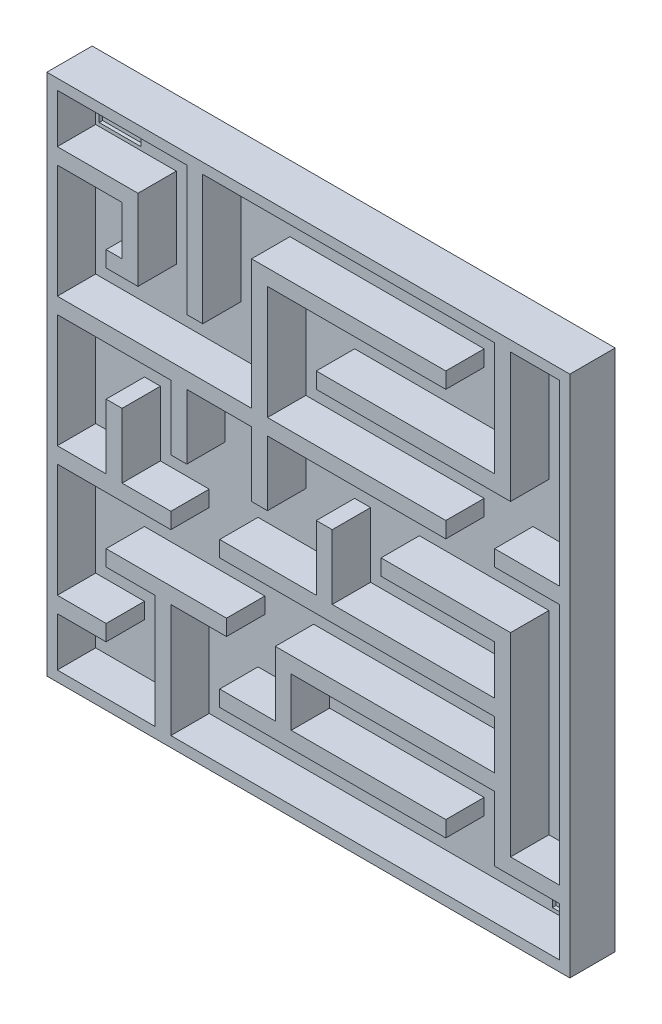
SolidWorks part; units mm, degrees
ref_plane "Front Plane" through (0, 0, 0) normal (0, 0, 1) x (1, 0, 0)
ref_plane "Top Plane" through (0, 0, 0) normal (0, 1, 0) x (1, 0, 0)
ref_plane "Right Plane" through (0, 0, 0) normal (1, 0, 0) x (0, 0, -1)
sketch "Sketch2" plane through (0, 0, 0) normal (0, 0, 1) x (1, 0, 0)
  line L1 (0, 0) -> (150, 0)
  line L2 (0, 0) -> (0, -150)
  line L3 (0, -150) -> (150, -150)
  line L4 (150, 0) -> (150, -150)
  dimension "D1" = 150
extrude "Boss-Extrude1" add sketch "Sketch2" along normal blind 2
sketch "Sketch3" plane through (0, 0, 2) normal (0, 0, 1) x (1, 0, 0)
  line L0 (140, -133) -> (140, -128.4286) construction
  line L1 (0, -3) -> (3, -3)
  line L2 (0, -3) -> (0, -150)
  line L3 (0, -150) -> (3, -150)
  line L4 (3, -3) -> (3, -150)
  line L5 (150, -150) -> (150, 0) construction
  line L10 (3, -147) -> (150, -147)
  line L15 (150, -147) -> (147, -147)
  line L16 (150, -147) -> (150, -3)
  line L17 (150, -3) -> (147, -3)
  line L18 (147, -147) -> (147, -3)
  line L19 (3, -147) -> (3, -150)
  line L20 (3, -150) -> (150, -150)
  line L21 (150, -147) -> (150, -150)
  line L22 (0, 0) -> (150, 0)
  line L23 (0, 0) -> (0, -3)
  line L24 (0, -3) -> (150, -3)
  line L25 (150, 0) -> (150, -3)
  line L26 (3, -17) -> (21.5714, -17)
  line L27 (3, -17) -> (3, -21.5714)
  line L28 (3, -21.5714) -> (21.5714, -21.5714)
  line L29 (21.5714, -17) -> (21.5714, -21.5714)
  line L30 (40.1429, -3) -> (44.7143, -3)
  line L31 (40.1429, -3) -> (40.1429, -40.1429)
  line L32 (40.1429, -40.1429) -> (44.7143, -40.1429)
  line L33 (44.7143, -3) -> (44.7143, -40.1429)
  line L34 (21.5714, -17) -> (26.1429, -17)
  line L35 (21.5714, -17) -> (21.5714, -35.5714)
  line L36 (21.5714, -35.5714) -> (26.1429, -35.5714)
  line L37 (26.1429, -17) -> (26.1429, -35.5714)
  line L38 (26.1429, -35.5714) -> (17, -35.5714)
  line L39 (26.1429, -35.5714) -> (26.1429, -40.1429)
  line L40 (26.1429, -40.1429) -> (17, -40.1429)
  line L41 (17, -35.5714) -> (17, -40.1429)
  line L42 (3, -54.1429) -> (114.4286, -54.1429)
  line L43 (3, -54.1429) -> (3, -58.7143)
  line L44 (3, -58.7143) -> (114.4286, -58.7143)
  line L45 (114.4286, -54.1429) -> (114.4286, -58.7143)
  line L46 (58.7143, -54.1429) -> (63.2857, -54.1429)
  line L47 (58.7143, -54.1429) -> (58.7143, -21.5714)
  line L48 (58.7143, -21.5714) -> (63.2857, -21.5714)
  line L49 (63.2857, -54.1429) -> (63.2857, -21.5714)
  line L50 (58.7143, -21.5714) -> (114.4286, -21.5714)
  line L51 (58.7143, -21.5714) -> (58.7143, -17)
  line L52 (58.7143, -17) -> (114.4286, -17)
  line L53 (114.4286, -21.5714) -> (114.4286, -17)
  line L54 (128.4286, -3) -> (133, -3)
  line L55 (128.4286, -3) -> (128.4286, -40.1429)
  line L56 (128.4286, -40.1429) -> (133, -40.1429)
  line L57 (133, -3) -> (133, -40.1429)
  line L66 (128.4286, -54.1429) -> (147, -54.1429)
  line L67 (128.4286, -54.1429) -> (128.4286, -58.7143)
  line L68 (128.4286, -58.7143) -> (147, -58.7143)
  line L69 (147, -54.1429) -> (147, -58.7143)
  line L70 (128.4286, -40.1429) -> (77.2857, -40.1429)
  line L71 (128.4286, -40.1429) -> (128.4286, -35.5714)
  line L72 (128.4286, -35.5714) -> (77.2857, -35.5714)
  line L73 (77.2857, -40.1429) -> (77.2857, -35.5714)
  line L74 (95.8571, -72.7143) -> (128.4286, -72.7143)
  line L75 (95.8571, -72.7143) -> (95.8571, -77.2857)
  line L76 (95.8571, -77.2857) -> (128.4286, -77.2857)
  line L77 (128.4286, -72.7143) -> (128.4286, -77.2857)
  line L78 (128.4286, -72.7143) -> (133, -72.7143)
  line L79 (128.4286, -72.7143) -> (128.4286, -133)
  line L80 (128.4286, -133) -> (133, -133)
  line L81 (133, -72.7143) -> (133, -133)
  line L82 (133, -133) -> (147, -133)
  line L83 (133, -133) -> (133, -128.4286)
  line L84 (133, -128.4286) -> (147, -128.4286)
  line L85 (147, -133) -> (147, -128.4286)
  line L86 (128.4286, -95.8571) -> (49.5714, -95.8571)
  line L87 (128.4286, -95.8571) -> (128.4286, -91.2857)
  line L88 (128.4286, -91.2857) -> (49.5714, -91.2857)
  line L89 (49.5714, -95.8571) -> (49.5714, -91.2857)
  line L90 (77.2857, -91.2857) -> (81.8571, -91.2857)
  line L91 (77.2857, -91.2857) -> (77.2857, -72.7143)
  line L92 (77.2857, -72.7143) -> (81.8571, -72.7143)
  line L93 (81.8571, -91.2857) -> (81.8571, -72.7143)
  line L94 (35.5714, -58.7143) -> (40.1429, -58.7143)
  line L95 (35.5714, -58.7143) -> (35.5714, -77.2857)
  line L96 (35.5714, -77.2857) -> (40.1429, -77.2857)
  line L97 (40.1429, -58.7143) -> (40.1429, -77.2857)
  line L98 (35.5714, -95.8571) -> (3, -95.8571)
  line L99 (35.5714, -95.8571) -> (35.5714, -91.2857)
  line L100 (35.5714, -91.2857) -> (3, -91.2857)
  line L101 (3, -95.8571) -> (3, -91.2857)
  line L102 (17, -91.2857) -> (21.5714, -91.2857)
  line L103 (17, -91.2857) -> (17, -72.7143)
  line L104 (17, -72.7143) -> (21.5714, -72.7143)
  line L105 (21.5714, -91.2857) -> (21.5714, -72.7143)
  line L106 (35.5714, -109.8571) -> (31, -109.8571)
  line L107 (35.5714, -109.8571) -> (35.5714, -147)
  line L108 (35.5714, -147) -> (31, -147)
  line L109 (31, -109.8571) -> (31, -147)
  line L110 (31, -109.8571) -> (17, -109.8571)
  line L111 (31, -109.8571) -> (31, -114.4286)
  line L112 (31, -114.4286) -> (17, -114.4286)
  line L113 (17, -109.8571) -> (17, -114.4286)
  line L114 (3, -128.4286) -> (17, -128.4286)
  line L115 (3, -128.4286) -> (3, -133)
  line L116 (3, -133) -> (17, -133)
  line L117 (17, -128.4286) -> (17, -133)
  line L122 (114.4286, -133) -> (65.5253, -133)
  line L123 (114.4286, -133) -> (114.4286, -128.4286)
  line L124 (114.4286, -128.4286) -> (65.5253, -128.4286)
  line L125 (65.5253, -133) -> (65.5253, -128.4286)
  line L126 (65.5253, -128.4286) -> (70.0967, -128.4286)
  line L127 (65.5253, -128.4286) -> (65.5253, -109.8571)
  line L128 (65.5253, -109.8571) -> (70.0967, -109.8571)
  line L129 (70.0967, -128.4286) -> (70.0967, -109.8571)
  line L130 (70.0967, -109.8571) -> (128.4286, -109.8571)
  line L131 (70.0967, -109.8571) -> (70.0967, -114.4286)
  line L132 (70.0967, -114.4286) -> (128.4286, -114.4286)
  line L133 (128.4286, -109.8571) -> (128.4286, -114.4286)
  line L134 (58.7143, -58.7143) -> (63.2857, -58.7143)
  line L135 (58.7143, -58.7143) -> (58.7143, -77.2857)
  line L136 (58.7143, -77.2857) -> (63.2857, -77.2857)
  line L137 (63.2857, -58.7143) -> (63.2857, -77.2857)
  line L138 (99.2626, -109.8571) -> (99.2626, -114.4286) construction
  line L140 (35.5714, -109.8571) -> (51.5253, -109.8571)
  line L141 (35.5714, -109.8571) -> (35.5714, -114.4286)
  line L142 (35.5714, -114.4286) -> (51.5253, -114.4286)
  line L143 (51.5253, -109.8571) -> (51.5253, -114.4286)
  line L144 (65.5253, -133) -> (49.5714, -133)
  line L145 (65.5253, -133) -> (65.5253, -128.4286)
  line L146 (65.5253, -128.4286) -> (49.5714, -128.4286)
  line L147 (49.5714, -133) -> (49.5714, -128.4286)
  line M25 (0, 0) -> (0, -150)
  line M26 (0, -150) -> (150, -150)
  dimension "D1" = 3
  dimension "D2" = 14
  dimension "D3" = 14
  dimension "D4" = 14
  dimension "D5" = 14
  dimension "D6" = 14
  dimension "D7" = 14
  dimension "D8" = 14
  dimension "D9" = 14
  dimension "D11" = 14
  dimension "D12" = 14
  dimension "D13" = 14
  dimension "D14" = 14
  dimension "D15" = 14
  dimension "D16" = 14
  dimension "D17" = 14
  dimension "D18" = 14
  dimension "D19" = 14
  dimension "D20" = 14
  dimension "D21" = 14
  dimension "D22" = 14
  dimension "D23" = 14
  dimension "D24" = 14
  dimension "D25" = 14
  dimension "D26" = 14
  dimension "D27" = 14
  dimension "D29" = 14
  dimension "D10" = 14
  dimension "D31" = 14
  dimension "D32" = 14
  dimension "D33" = 14
  dimension "D28" = 14
  dimension "D30" = 14
extrude "Boss-Extrude2" add sketch "Sketch3" along normal blind 11 contours L50 L53 L52 L51 L48 | L42 L49 L48 L47 | L73 L70 L55 L72 | L57 L24 L55 L56 | L67 L68 L18 L66 | L81 L78 L77 L79 L80 | L88 L93 L92 L91 | L89 L86 L79 L88 | L99 L100 L4 L98 | L117 L114 L4 L116 | L110 L113 L112 L109 | L129 L132 L79 L130 | L124 L129 L128 L127 | L125 L122 L123 L124 | L4 L1 M25 M26
sketch "Sketch4" plane through (0, 0, 2) normal (0, 0, 1) x (1, 0, 0)
  line L1 (16, -16) -> (4, -16)
  line L2 (16, -16) -> (16, -4)
  line L3 (16, -4) -> (4, -4)
  line L4 (4, -16) -> (4, -4)
  line L5 (3, -10) -> (4, -10) construction
  line L6 (3, -3) -> (3, -17) construction
  line L7 (10, -16) -> (10, -17) construction
  line L8 (3, -17) -> (26.1429, -17) construction
  line L9 (140, -133) -> (140, -134) construction
  line L10 (134, -134) -> (146, -134)
  line L11 (134, -134) -> (134, -146)
  line L12 (134, -146) -> (146, -146)
  line L13 (146, -134) -> (146, -146)
  line L15 (146, -140) -> (147, -140) construction
  line L17 (128.4286, -133) -> (147, -133) construction
  line L18 (147, -147) -> (147, -133) construction
  dimension "D1" = 12
  dimension "D2" = 12
extrude "Cut-Extrude1" cut sketch "Sketch4" against normal offset from surface (1 mm away) 1 up to face at (75, -75, 0)
sketch "Sketch5" plane through (0, 0, 2) normal (0, 0, 1) x (1, 0, 0)
  line L0 (3, -147) -> (147, -3) construction
sketch "Sketch6" plane through (0, 0, 2) normal (0, 0, 1) x (1, 0, 0)
  line L0 (4, -4) -> (16, -16) construction
  line L2 (10, -10) -> (0, -10) construction
  line L3 (0, 0) -> (0, -150) construction
  line L4 (10, -10) -> (10, 0) construction
  line L5 (0, 0) -> (150, 0) construction
equation "\"x\"= 1.4"
equation "\"D25@Sketch3\"=\"x\""
equation "\"D27@Sketch3\"=\"x\""
equation "\"D29@Sketch3\"=\"x\""
equation "\"D24@Sketch3\"=\"x\""
equation "\"D26@Sketch3\"=\"x\""
equation "\"D20@Sketch3\"=\"x\""
equation "\"D21@Sketch3\"=\"x\""
equation "\"D22@Sketch3\"=\"x\""
equation "\"D23@Sketch3\"=\"x\""
equation "\"D19@Sketch3\"=\"x\""
equation "\"D16@Sketch3\"=\"x\""
equation "\"D18@Sketch3\"=\"x\""
equation "\"D17@Sketch3\"=\"x\""
equation "\"D12@Sketch3\"=\"x\""
equation "\"D9@Sketch3\"=\"x\""
equation "\"D15@Sketch3\"=\"x\""
equation "\"D11@Sketch3\"=\"x\""
equation "\"D13@Sketch3\"=\"x\""
equation "\"D2@Sketch3\"=\"x\""
equation "\"D6@Sketch3\"=\"x\""
equation "\"D3@Sketch3\"=\"x\""
equation "\"D5@Sketch3\"=\"x\""
equation "\"D4@Sketch3\"=\"x\""
equation "\"D7@Sketch3\"=\"x\""
equation "\"D8@Sketch3\"=\"x\""
equation "\"D14@Sketch3\"=\"x\""
equation "\"D10@Sketch3\"=\"x\""
equation "\"D31@Sketch3\"=\"x\""
equation "\"D32@Sketch3\"=\"x\""
equation "\"D33@Sketch3\"=\"x\""
equation "\"D28@Sketch3\"=\"x\""
equation "\"D30@Sketch3\"=\"x\""
